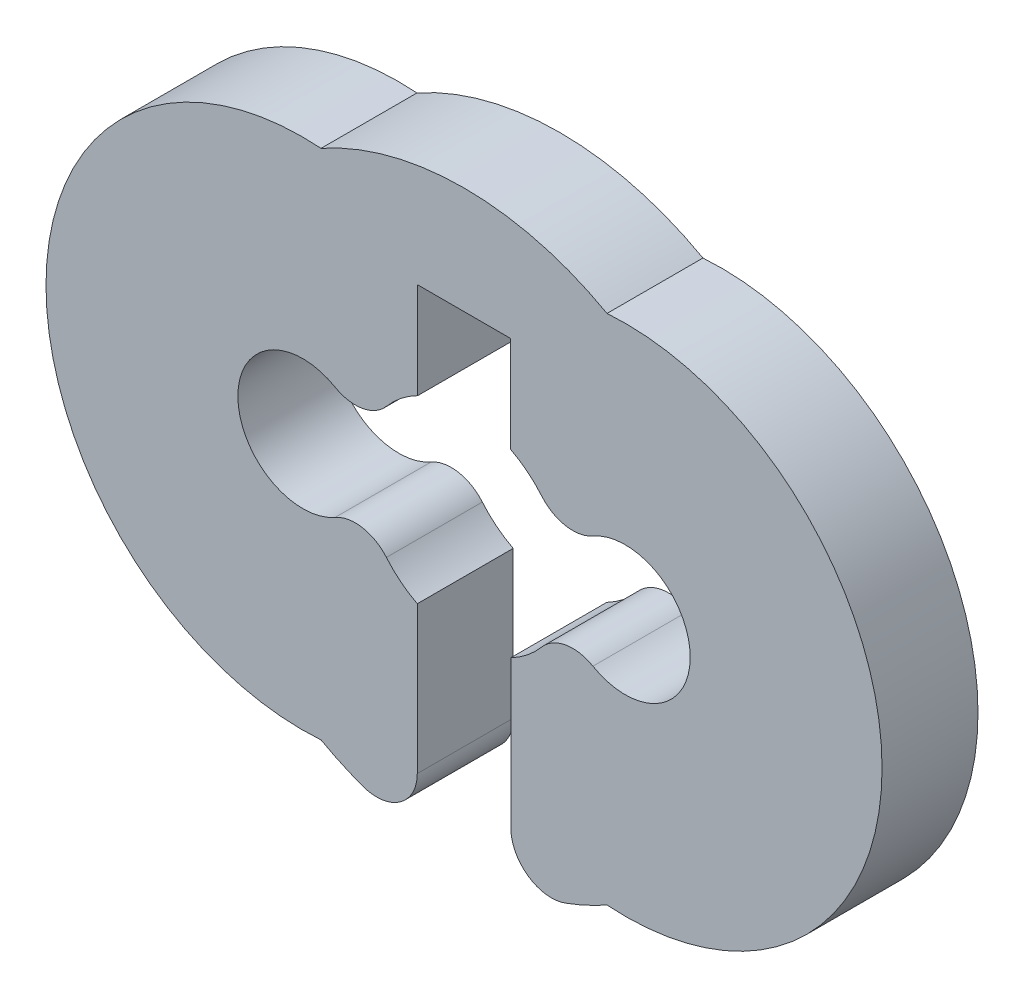
SolidWorks part; units mm, degrees
material "Acrylic (Medium-high impact)"
ref_plane "Front Plane" through (0, 0, 0) normal (0, 0, 1) x (1, 0, 0)
ref_plane "Top Plane" through (0, 0, 0) normal (0, 1, 0) x (1, 0, 0)
ref_plane "Right Plane" through (0, 0, 0) normal (1, 0, 0) x (0, 0, -1)
sketch "스케치1" plane through (0, 0, 0) normal (0, 0, 1) x (1, 0, 0)
  line L0 (0, 10.85) -> (0, 0) construction
  line L5 (-3.1109, 0.635) -> (-3.1109, -0.635) construction
  line L6 (-1.4475, 5.8258) -> (1.4475, 5.8258)
  line L7 (0, 0) -> (0, -5.9379) construction
  line L8 (-1.4625, -9.0577) -> (1.4625, -9.0577) construction
  line L9 (-1.4625, -9.0577) -> (-1.4625, -2.8181)
  line L10 (-1.4625, -2.8181) -> (1.4625, -2.8181) construction
  line L11 (1.4625, -9.0577) -> (1.4625, -2.8181)
  line L12 (-1.4625, -9.0577) -> (1.4625, -2.8181) construction
  line L13 (-1.4625, -2.8181) -> (1.4625, -9.0577) construction
  line L14 (-1.4475, 5.8258) -> (-1.4475, 2.8258)
  line L15 (-1.4475, 2.8258) -> (1.4475, 2.8258) construction
  line L16 (1.4475, 5.8258) -> (1.4475, 2.8258)
  line L17 (-1.4475, 5.8258) -> (1.4475, 2.8258) construction
  line L18 (-1.4475, 2.8258) -> (1.4475, 5.8258) construction
  line L19 (-3.1109, 0) -> (0, 0) construction
  circle A0 centre (0, 0) radius 9.175 construction
  circle A1 centre (0, 0) radius 3.175 construction
  arc A2 (-1.4625, -9.0577) -> (1.4625, -9.0577) centre (0, 0) cw construction
  arc A3 (1.4625, -2.8181) -> (1.4475, 2.8258) centre (0, 0) ccw construction
  arc A4 (-1.4475, 2.8258) -> (-1.4625, -2.8181) centre (0, 0) ccw construction
  arc A5 (-4.4713, 8.0118) -> (-4.4713, -8.0118) centre (-5.0411, 0) ccw
  arc A6 (-3.1109, 0.635) -> (-3.1109, -0.635) centre (-5.0411, 0) ccw construction
  arc A7 (-3.1109, 0.635) -> (-3.1109, -0.635) centre (-5.0411, 0) ccw
  arc A8 (-3.1109, 0.635) -> (-1.4475, 2.8258) centre (0, 0) cw
  arc A9 (-3.1109, -0.635) -> (-1.4625, -2.8181) centre (0, 0) ccw
  arc A10 (-4.4713, -8.0118) -> (-1.4625, -9.0577) centre (0, 0) ccw
  arc A11 (3.1109, 0.635) -> (1.4475, 2.8258) centre (0, 0) ccw
  arc A12 (3.1109, -0.635) -> (1.4625, -2.8181) centre (0, 0) cw
  arc A13 (3.1109, 0.635) -> (3.1109, -0.635) centre (5.0411, 0) cw
  arc A14 (4.4713, -8.0118) -> (1.4625, -9.0577) centre (0, 0) cw
  arc A15 (4.4713, 8.0118) -> (4.4713, -8.0118) centre (5.0411, 0) cw
  arc A16 (-4.4713, 8.0118) -> (4.4713, 8.0118) centre (0, 0) cw
  point P2 (0, 10.85)
  point P5 (0, 4.3258)
  point P10 (0, -5.9379)
  dimension "D1" = 6
  dimension "D2" = 6.35
  dimension "D6" = 6
  dimension "D7" = 2.032
  dimension "D3" = 2.895
  dimension "D4" = 3
  dimension "D5" = 2.925
  dimension "D8" = 1.27
extrude "보스-돌출1" add sketch "스케치1" along normal blind 3
fillet "필렛1" radius 1.27 6 edges at (1.4625, -9.0577, 1.5) (-1.4625, -9.0577, 1.5) (-3.1109, -0.635, 1.5) (3.1109, -0.635, 1.5) (3.1109, 0.635, 1.5) (-3.1109, 0.635, 1.5)
